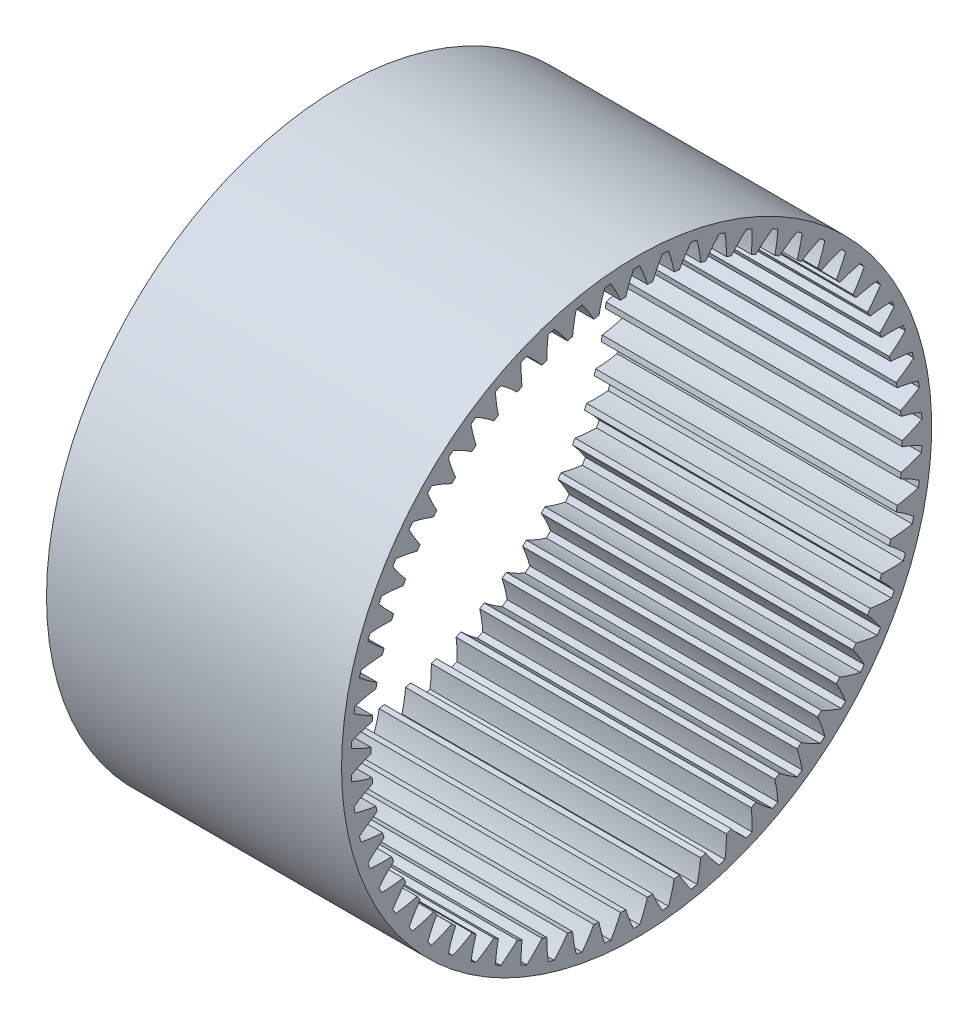
SolidWorks part; units mm, degrees
ref_plane "Plane1" through (0, 0, 0) normal (0, 0, 1) x (1, 0, 0)
ref_plane "Plane2" through (0, 0, 0) normal (0, 1, 0) x (1, 0, 0)
ref_plane "Plane3" through (0, 0, 0) normal (1, 0, 0) x (0, 0, -1)
other "Configuration Table"
sketch "HoldingSke" plane through (0, 0, 0) normal (0, 1, 0) x (1, 0, 0)
  line L0 (0, 0) -> (0.7825, -1.4716)
  line L1 (-15, 0) -> (100, 0) construction
  line L2 (0, 0) -> (-2.1039, 2.3779)
  line L3 (0, 0) -> (-11.863, 4.5341)
  line L4 (0, 0) -> (4.0544, 7.6251)
  line L5 (0, 0) -> (-23.7986, -8.8762)
  line L6 (0, 0) -> (-10.5278, -7.1032)
  line L7 (-2.1039, 2.3779) -> (3.3635, 27.1825)
  line L8 (-76.2, 2.9779) -> (-54.61, 2.9779)
  line L9 (-71.009, 38.7566) -> (-53.1078, 45.2721)
  line L10 (-76.2, 71.12) -> (104.1128, 71.12)
  line L11 (0, 0) -> (-20, 0)
  line L12 (-76.2, 101.6) -> (-76.177, 101.6)
  line L13 (24.9733, 27.94) -> (52.9518, 28.4284)
  line L14 (24.9733, 27.94) -> (24.9743, 27.94)
  line L15 (24.9733, 27.94) -> (100.4006, 29.5858)
  circle A0 centre (0, 0) radius 20
  circle A1 centre (0, 0) radius 12.7
  circle A2 centre (0, 0) radius 12.7
  dimension "MHD" = 25.4
  dimension "Hub_dia" = 25.4
  dimension "Diameter" = 40
  dimension "Num_teeth" = 62
  dimension "Pitch" = 1.6667
  dimension "Overall_len" = 25.4
  dimension "Show_teeth" = 62
  dimension "Thickness" = 12.7
  dimension "OAL" = 25.4001
  dimension "T_dim" = 21.59
  dimension "Ap" = 20
  dimension "H" = 19.05
  dimension "Pitch_radius" = 180.3128
  dimension "Width" = 20
  dimension "Backlash" = 0.023
  dimension "Addendum_fac" = 1
  dimension "Dedendum_fac" = 1.25
  dimension "Clearance_fac" = 0.25
  dimension "Dedendum_add" = 0.001
  dimension "Module" = 0.6
sketch "BasProSke" plane through (0, 0, 0) normal (0, 1, 0) x (1, 0, 0)
  line L0 (-10, 0) -> (60, 0) construction
  line L1 (0, 18) -> (0, 20)
  line L2 (0, 18) -> (20, 18)
  line L3 (20, 18) -> (20, 20)
  line L4 (20, 20) -> (0, 20)
  dimension "Diameter" = 40
  dimension "Thickness" = 20
  dimension "Inside_diameter" = 36
revolve "Base-Revolve" add sketch "BasProSke" angle 360 about L0
sketch "TooCutSke" plane through (0, 0, 0) normal (1, 0, 0) x (0, 0, -1)
  line L3 (0.5287, 18.5925) -> (0.5287, 53.6633) construction
  line L4 (0, 0) -> (0, 59.563) construction
  line L5 (0, 0) -> (-3.4607, 68.2398) construction
  line L6 (-8.1824, 15.3357) -> (36.9975, 17.627) construction
  circle A0 centre (0, 0) radius 18.6 construction
  circle A1 centre (0, 0) radius 19.351 construction
  circle A2 centre (0, 0) radius 15.7305 construction
  circle A3 centre (0, 0) radius 17.9746 construction
  arc A4 (0.7398, 17.9594) -> (0.2066, 19.3499) centre (-8.1824, 15.3357) ccw
  arc A5 (0.7398, 17.9594) -> (-0.7398, 17.9594) centre (0, 0) ccw
  arc A6 (0.2066, 19.3499) -> (-0.2066, 19.3499) centre (0, 0) ccw
  arc A7 (-0.2066, 19.3499) -> (-0.7398, 17.9594) centre (8.1824, 15.3357) ccw
  dimension "Pitch_dia" = 37.2
  dimension "Base_dia" = 31.4609
  dimension "Root_dia" = 38.702
  dimension "Overcut_dia" = 35.9492
  dimension "Flank_rad" = 9.3
  dimension "Half_ang" = 2.903
  dimension "Half_CT" = 0.5287
extrude "ToothCut" cut sketch "TooCutSke" along normal through all
fillet "Breaks" [suppressed] radius 0.06
fillet "RootFillets" [suppressed] radius 0.151
pattern_circular "TeethCuts" count 62 every 5.806 about axis through (-10, 0, 0) along (1, 0, 0) of "RootFillets", "Breaks", "ToothCut"
equation "' \"Module@HoldingSke\" = 6.35"
equation "' \"Num_teeth@HoldingSke\" = 24"
equation "' \"Ap@HoldingSke\" =  14.5"
equation "' \"Ap@HoldingSke\" = 14.5"
equation "' \"Width@HoldingSke\" = 12"
equation "' \"Diameter@HoldingSke\" = 8 * 25.4"
equation "' \"Show_teeth@HoldingSke\" = 100"
equation "' \"Backlash@HoldingSke\" = 0.009 * 25.4"
equation "' \"Addendum_fac@HoldingSke\" = 1.0"
equation "' \"Dedendum_fac@HoldingSke\" = 1.25"
equation "' \"Dedendum_add@HoldingSke\" = 0.00005 * 25.4"
equation "' \"Clearance_fac@HoldingSke\" = 0.25"
equation "\"Pitch@HoldingSke\" = 1 / \"Module@HoldingSke\" "
equation "\"Overcut_dia@TooCutSke\" = (\"Num_teeth@HoldingSke\" - 2 * \"Addendum_fac@HoldingSke\") / \"Pitch@HoldingSke\" - 0.002 * 25.4"
equation "\"Pitch_dia@TooCutSke\" = \"Num_teeth@HoldingSke\" / \"Pitch@HoldingSke\""
equation "\"Base_dia@TooCutSke\" = \"Num_teeth@HoldingSke\" / \"Pitch@HoldingSke\" * cos((\"Ap@HoldingSke\"  * 3.14159265 / 180)) * 0.90"
equation "\"Root_dia@TooCutSke\" = \"Num_teeth@HoldingSke\"  / \"Pitch@HoldingSke\" + 2 *  \"Dedendum_fac@HoldingSke\"/ \"Pitch@HoldingSke\" + \"Dedendum_add@HoldingSke\" * 2"
equation "\"Half_ang@TooCutSke\" = 180 / \"Num_teeth@HoldingSke\""
equation "\"Half_CT@TooCutSke\" = \"Num_teeth@HoldingSke\" / \"Pitch@HoldingSke\" * sin((3.14159265 / 2 / \"Num_teeth@HoldingSke\")) / 2 + 10 * \"Backlash@HoldingSke\" / 4"
equation "\"Flank_rad@TooCutSke\" = \"Num_teeth@HoldingSke\" / \"Pitch@HoldingSke\" / 4"
equation "\"Radius@RootFillets\"= \"Clearance_fac@HoldingSke\" / \"Pitch@HoldingSke\" + \"Dedendum_add@HoldingSke\""
equation "\"Break_rad@Breaks\" = 0.02 / \"Pitch@HoldingSke\" * 5"
equation "\"Num_teeth@TeethCuts\" = int( \"Show_teeth@HoldingSke\" ) + 1"
equation "\"Num_teeth@TeethCuts\" = ((sgn( \"Num_teeth@TeethCuts\" - \"Num_teeth@HoldingSke\" )-1)*( \"Num_teeth@TeethCuts\" - \"Num_teeth@HoldingSke\" ))/-2+ \"Num_teeth@HoldingSke\""
equation "\"Num_teeth@TeethCuts\" = ((sgn( \"Num_teeth@TeethCuts\" - 2.0)+1)*( \"Num_teeth@TeethCuts\" - 2.0))/2 +2.0"
equation "\"Angle@TeethCuts\" = 360.0 / \"Num_teeth@HoldingSke\""
equation "\"Diameter@BasProSke\" = \"Num_teeth@HoldingSke\"  / \"Pitch@HoldingSke\" + 2 *  \"Dedendum_fac@HoldingSke\"/ \"Pitch@HoldingSke\" + \"Dedendum_add@HoldingSke\" * 2 + 0.002 * 25.4"
equation "\"Diameter@BasProSke\" = ((sgn( \"Diameter@BasProSke\"  - \"Diameter@HoldingSke\" )+1)*( \"Diameter@BasProSke\"  - \"Diameter@HoldingSke\" ))/2 + \"Diameter@HoldingSke\""
equation "\"Inside_diameter@BasProSke\" =  (\"Num_teeth@HoldingSke\" - 2 * \"Addendum_fac@HoldingSke\") / \"Pitch@HoldingSke\" "
equation "\"Thickness@BasProSke\"  = \"Width@HoldingSke\""
